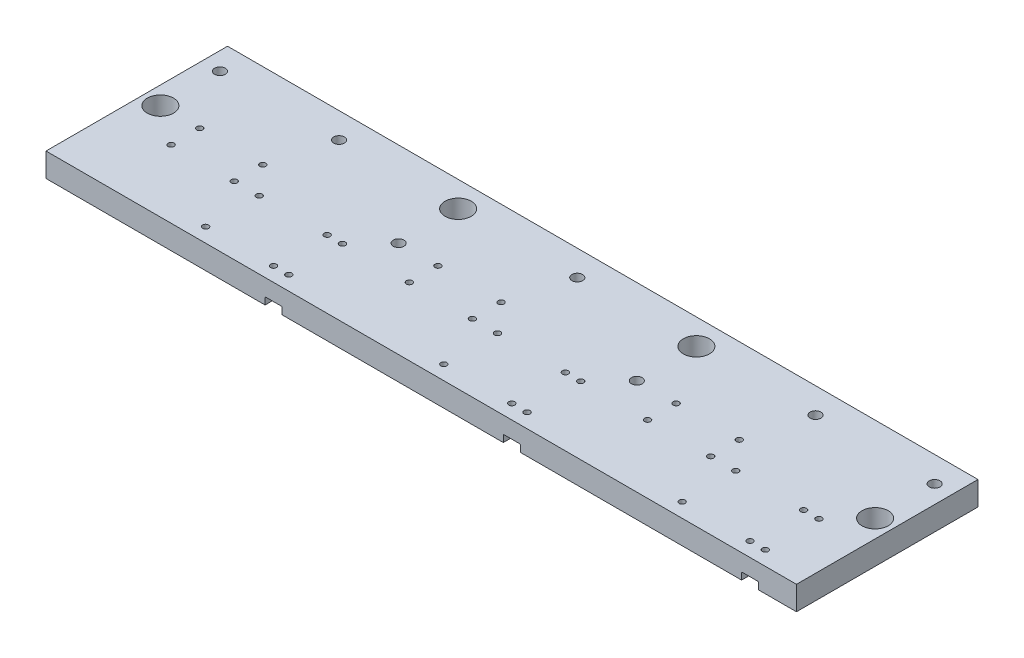
SolidWorks part; units mm, degrees
material "Low Carbon Steel"
ref_plane "Front Plane" through (0, 0, 0) normal (0, 0, 1) x (1, 0, 0)
ref_plane "Top Plane" through (0, 0, 0) normal (0, 1, 0) x (1, 0, 0)
ref_plane "Right Plane" through (0, 0, 0) normal (1, 0, 0) x (0, 0, -1)
sketch "Sketch1" plane through (0, 0, 0) normal (0, 1, 0) x (1, 0, 0)
  line L0 (-315, -76.2) -> (315, 76.2) construction
  line L1 (-315, -76.2) -> (315, -76.2)
  line L2 (-315, -76.2) -> (-315, 76.2)
  line L3 (-315, 76.2) -> (315, 76.2)
  line L4 (315, -76.2) -> (315, 76.2)
  dimension "D1" = 630
  dimension "D2" = 152.4
extrude "Boss-Extrude1" add sketch "Sketch1" along normal mid plane 25.4
sketch "Sketch8" plane through (0, 0, 76.2) normal (0, 0, -1) x (-1, 0, 0)
  line L0 (-83.2, -10) -> (-83.2, -4)
  line L1 (315, 12.7) -> (-315, 12.7)
  line L2 (-315, 12.7) -> (-315, 10)
  line L3 (131.0875, -10) -> (131.0875, -4)
  line L4 (315, 12.7) -> (315, 10)
  line L5 (-83.2, -4) -> (-68.9125, -4)
  line L6 (315, -12.7) -> (-315, -12.7)
  line L7 (315, -12.7) -> (315, -10)
  line L8 (315, -10) -> (131.0875, -10)
  line L9 (-315, -12.7) -> (-315, -10)
  line L10 (315, 12.7) -> (315, -12.7) construction
  line L11 (-315, 12.7) -> (-315, -12.7) construction
  line L12 (-68.9125, -4) -> (-68.9125, -10)
  line L13 (-315, -12.7) -> (315, -12.7) construction
  line L14 (131.0875, -4) -> (116.8, -4)
  line L15 (116.8, -4) -> (116.8, -10)
  line L16 (-283.2, -10) -> (-283.2, -4)
  line L17 (-283.2, -4) -> (-268.9125, -4)
  line L18 (-268.9125, -4) -> (-268.9125, -10)
  line L19 (-283.2, -10) -> (-315, -10)
  line L20 (-83.2, -10) -> (-268.9125, -10)
  line L21 (116.8, -10) -> (-68.9125, -10)
  line L25 (-315, 10) -> (315, 10)
  dimension "D1" = 20
  dimension "D2" = 116.8
  dimension "D3" = 200
  dimension "D4" = 14.2875
  dimension "D5" = 6
  dimension "D6" = 2.7
extrude "Cut-Extrude1" cut sketch "Sketch8" along normal through all
sketch "Sketch23" plane through (0, -10, 0) normal (0, -1, 0) x (1, 0, 0)
  line L0 (-116.8, 6.35) -> (-116.8, -76.2)
  line L1 (-116.8, -76.2) -> (-131.0875, -76.2)
  line L2 (-131.0875, -76.2) -> (-131.0875, 6.35)
  line L3 (-131.0875, -76.2) -> (-131.0875, 76.2) construction
  line L4 (-315, 76.2) -> (-131.0875, 76.2) construction
  line L5 (68.9125, 6.35) -> (68.9125, -76.2)
  line L6 (68.9125, -76.2) -> (68.9125, 76.2) construction
  line L7 (68.9125, -76.2) -> (83.2, -76.2)
  line L8 (83.2, -76.2) -> (83.2, 6.35)
  line L9 (83.2, -76.2) -> (83.2, 76.2) construction
  line L10 (268.9125, 6.35) -> (268.9125, -76.2)
  line L11 (268.9125, -76.2) -> (268.9125, 76.2) construction
  line L12 (268.9125, -76.2) -> (268.9125, 76.2) construction
  line L13 (83.2, -76.2) -> (268.9125, -76.2) construction
  line L14 (268.9125, -76.2) -> (283.2, -76.2)
  line L15 (283.2, -76.2) -> (283.2, 6.35)
  line L16 (283.2, -76.2) -> (283.2, 76.2) construction
  arc A0 (-131.0875, 6.35) -> (-116.8, 6.35) centre (-123.9438, 6.35) ccw
  arc A1 (68.9125, 6.35) -> (83.2, 6.35) centre (76.0563, 6.35) ccw
  arc A2 (268.9125, 6.35) -> (283.2, 6.35) centre (276.0562, 6.35) ccw
  dimension "D1" = 69.85
extrude "Boss-Extrude2" add sketch "Sketch23" against normal up to next
hole_wizard "M8 Clearance Hole1" positions "Sketch3" profile "Sketch2" hole size "M8" standard "Peddi DIN" end condition through all
sketch "Sketch3" plane through (-252.0858, -10, 54.7893) normal (0, -1, 0) x (-1, 0, 0)
  line L9 (-567.0858, -21.4107) -> (-535.2858, -21.4107) construction
  line L10 (-552.0858, 109.5893) -> (-452.0858, 109.5893) construction
  line L11 (-452.0858, 109.5893) -> (-252.0858, 109.5893) construction
  line L12 (-252.0858, 109.5893) -> (-52.0858, 109.5893) construction
  line L13 (-52.0858, 109.5893) -> (47.9142, 109.5893) construction
  line L15 (-252.0858, 109.5893) -> (-252.0858, 54.7893) construction
  line L17 (-352.0858, 59.5893) -> (-352.0858, 109.5893) construction
  line L19 (-152.0858, 59.5893) -> (-152.0858, 109.5893) construction
  point P0 (47.9142, 109.5893)
  point P2 (-52.0858, 109.5893)
  point P4 (-152.0858, 59.5893)
  point P6 (-252.0858, 109.5893)
  point P8 (-352.0858, 59.5893)
  point P10 (-452.0858, 109.5893)
  point P12 (-552.0858, 109.5893)
  dimension "D1" = 100
  dimension "D2" = 50
  dimension "D5" = 131
  dimension "D8" = 200
sketch "Sketch2" plane through (-300, -10, -54.8) normal (1, 0, 0) x (0, 0, -1)
  line L0 (0, 0) -> (0, 20)
  line L1 (0, 20) -> (4.5, 20)
  line L2 (4.5, 20) -> (4.5, 0)
  line L5 (4.5, 0) -> (0, 0)
  line L11 (0, -6.35) -> (0, 107.95) construction
  dimension "Thru Hole Dia." = 9
  dimension "Thru Hole Depth" = 20
hole_wizard "M20 Clearance Hole1" positions "Sketch5" profile "Sketch4" hole size "M20" standard "Peddi DIN" end condition through all
sketch "Sketch5" plane through (-106.6992, -10, 17.1349) normal (0, -1, 0) x (-1, 0, 0)
  line L17 (-406.6992, 71.9349) -> (-406.6992, 21.9349) construction
  line L18 (-406.6992, 21.9349) -> (-206.6992, 21.9349) construction
  line L20 (-206.6992, 21.9349) -> (-206.6992, 71.9349) construction
  line L21 (-206.6992, 71.9349) -> (-106.6992, 71.9349) construction
  line L23 (-106.6992, 71.9349) -> (-6.6992, 71.9349) construction
  line L24 (-6.6992, 71.9349) -> (-6.6992, 21.9349) construction
  line L25 (-6.6992, 21.9349) -> (193.3008, 21.9349) construction
  line L26 (193.3008, 21.9349) -> (193.3008, 71.9349) construction
  point P52 (-406.6992, 21.9349)
  point P61 (-206.6992, 71.9349)
  point P73 (-6.6992, 71.9349)
  point P78 (193.3008, 21.9349)
sketch "Sketch4" plane through (-300, -10, -4.8) normal (1, 0, 0) x (0, 0, -1)
  line L0 (0, 0) -> (0, 20)
  line L1 (0, 20) -> (11, 20)
  line L2 (11, 20) -> (11, 0)
  line L5 (11, 0) -> (0, 0)
  line L11 (0, -6.35) -> (0, 107.95) construction
  dimension "Thru Hole Dia." = 22
  dimension "Thru Hole Depth" = 20
hole_wizard "M6 Tapped Hole2" positions "Sketch7" profile "Sketch6" tap size "M6" standard "Peddi DIN"
sketch "Sketch7" plane through (-22.8298, -10, 14.4386) normal (0, -1, 0) x (-1, 0, 0)
  line L21 (-155.8298, -4.7614) -> (-208.8298, -4.7614) construction
  line L22 (-155.8298, -4.7614) -> (-155.8298, 19.2386) construction
  line L23 (-155.8298, 19.2386) -> (-208.8298, 19.2386) construction
  line L24 (-208.8298, -4.7614) -> (-208.8298, 19.2386) construction
  line L26 (-229.8298, -49.7614) -> (-286.8298, -49.7614) construction
  line L27 (-229.8298, -49.7614) -> (-229.8298, -4.7614) construction
  line L28 (-229.8298, -4.7614) -> (-286.8298, -4.7614) construction
  line L29 (-286.8298, -49.7614) -> (-286.8298, -4.7614) construction
  line L37 (-337.8298, -61.7614) -> (-337.8298, 90.6386) construction
  line L40 (-106.0298, -61.7614) -> (-291.7423, -61.7614) construction
  line L41 (-208.8298, 7.2386) -> (-155.8298, 7.2386) construction
  point P110 (-155.8298, -4.7614)
  point P111 (-208.8298, 19.2386)
  point P140 (-155.8298, 19.2386)
  point P141 (-208.8298, -4.7614)
  point P142 (-229.8298, -49.7614)
  point P143 (-286.8298, -4.7614)
  point P168 (-229.8298, -4.7614)
  point P169 (-286.8298, -49.7614)
  dimension "D2" = 78
  dimension "D3" = 53
  dimension "D4" = 57
  dimension "D5" = 45
  dimension "D6" = 12
  dimension "D7" = 24
  dimension "D12" = 51
sketch "Sketch6" plane through (133, -10, 19.2) normal (1, 0, 0) x (0, 0, -1)
  line L0 (0, 0) -> (0, 29.4922)
  line L1 (0, 29.4922) -> (2.5, 27.99)
  line L2 (2.5, 27.99) -> (2.5, 0)
  line L5 (2.5, 0) -> (0, 0)
  line L10 (0, 29.4922) -> (-2.5, 27.99) construction
  line L11 (0, -6.35) -> (0, 107.95) construction
  dimension "Tap Drill Dia." = 5
  dimension "Tap Drill Depth" = 27.99
  dimension "Drill Angle" = 118
cosmetic thread "Hole Thread1" parameters "D1"=15.01, "D2"=6
cosmetic thread "Hole Thread2" parameters "D1"=15.01, "D2"=6
cosmetic thread "Hole Thread3" parameters "D1"=15.01, "D2"=6
cosmetic thread "Hole Thread4" parameters "D1"=15.01, "D2"=6
cosmetic thread "Hole Thread5" parameters "D1"=15.01, "D2"=6
cosmetic thread "Hole Thread6" parameters "D1"=15.01, "D2"=6
cosmetic thread "Hole Thread7" parameters "D1"=15.01, "D2"=6
cosmetic thread "Hole Thread8" parameters "D1"=15.01, "D2"=6
hole_wizard "M6 Tapped Hole5" positions "Sketch15" profile "Sketch16" tap size "M6" standard "Peddi DIN"
sketch "Sketch15" plane through (0, -10, 0) normal (0, -1, 0) x (-1, 0, 0)
  line L1 (14, 4.8) -> (67, 4.8) construction
  line L2 (14, 4.8) -> (14, -19.2) construction
  line L3 (14, -19.2) -> (67, -19.2) construction
  line L4 (67, 4.8) -> (67, -19.2) construction
  line L6 (-64, -19.2) -> (-7, -19.2) construction
  line L7 (-64, -19.2) -> (-64, -64.2) construction
  line L8 (-64, -64.2) -> (-7, -64.2) construction
  line L9 (-7, -19.2) -> (-7, -64.2) construction
  line L10 (-186, -19.2) -> (-186, 4.8) construction
  line L11 (-264, -64.2) -> (-264, -19.2) construction
  line L12 (-207, -19.2) -> (-264, -19.2) construction
  line L13 (-207, -64.2) -> (-264, -64.2) construction
  line L14 (-133, -19.2) -> (-186, -19.2) construction
  line L15 (-133, 4.8) -> (-186, 4.8) construction
  point P1 (14, 4.8)
  point P2 (67, -19.2)
  point P5 (14, -19.2)
  point P6 (67, 4.8)
  point P41 (-64, -19.2)
  point P42 (-7, -64.2)
  point P45 (-64, -64.2)
  point P46 (-7, -19.2)
  dimension "D1" = 200
  dimension "D2" = 200
sketch "Sketch16" plane through (-14, -10, -4.8) normal (1, 0, 0) x (0, 0, -1)
  line L0 (0, 0) -> (0, 29.4922)
  line L1 (0, 29.4922) -> (2.5, 27.99)
  line L2 (2.5, 27.99) -> (2.5, 0)
  line L5 (2.5, 0) -> (0, 0)
  line L10 (0, 29.4922) -> (-2.5, 27.99) construction
  line L11 (0, -6.35) -> (0, 107.95) construction
  dimension "Tap Drill Dia." = 5
  dimension "Tap Drill Depth" = 27.99
  dimension "Drill Angle" = 118
cosmetic thread "Hole Thread43" parameters "D1"=15.01, "D2"=6
cosmetic thread "Hole Thread44" parameters "D1"=15.01, "D2"=6
cosmetic thread "Hole Thread45" parameters "D1"=15.01, "D2"=6
cosmetic thread "Hole Thread46" parameters "D1"=15.01, "D2"=6
cosmetic thread "Hole Thread47" parameters "D1"=15.01, "D2"=6
cosmetic thread "Hole Thread48" parameters "D1"=15.01, "D2"=6
cosmetic thread "Hole Thread49" parameters "D1"=15.01, "D2"=6
cosmetic thread "Hole Thread50" parameters "D1"=15.01, "D2"=6
hole_wizard "M6 Tapped Hole6" positions "Sketch17" profile "Sketch18" tap size "M6" standard "Peddi DIN"
sketch "Sketch17" plane through (0, -10, 0) normal (0, -1, 0) x (-1, 0, 0)
  line L1 (136, -19.2) -> (193, -19.2) construction
  line L2 (136, -19.2) -> (136, -64.2) construction
  line L3 (136, -64.2) -> (193, -64.2) construction
  line L4 (193, -19.2) -> (193, -64.2) construction
  line L6 (214, 4.8) -> (267, 4.8) construction
  line L7 (214, 4.8) -> (214, -19.2) construction
  line L8 (214, -19.2) -> (267, -19.2) construction
  line L9 (267, 4.8) -> (267, -19.2) construction
  line L10 (-207, -19.2) -> (-264, -19.2) construction
  line L11 (-133, 4.8) -> (-186, 4.8) construction
  line L12 (-133, -19.2) -> (-186, -19.2) construction
  line L13 (-207, -64.2) -> (-264, -64.2) construction
  line L14 (-264, -64.2) -> (-264, -19.2) construction
  line L15 (-186, -19.2) -> (-186, 4.8) construction
  point P1 (136, -19.2)
  point P2 (193, -64.2)
  point P5 (136, -64.2)
  point P6 (193, -19.2)
  point P87 (214, 4.8)
  point P88 (267, -19.2)
  point P91 (214, -19.2)
  point P92 (267, 4.8)
  dimension "D1" = 400
  dimension "D2" = 400
sketch "Sketch18" plane through (-136, -10, 19.2) normal (1, 0, 0) x (0, 0, -1)
  line L0 (0, 0) -> (0, 29.4922)
  line L1 (0, 29.4922) -> (2.5, 27.99)
  line L2 (2.5, 27.99) -> (2.5, 0)
  line L5 (2.5, 0) -> (0, 0)
  line L10 (0, 29.4922) -> (-2.5, 27.99) construction
  line L11 (0, -6.35) -> (0, 107.95) construction
  dimension "Tap Drill Dia." = 5
  dimension "Tap Drill Depth" = 27.99
  dimension "Drill Angle" = 118
cosmetic thread "Hole Thread51" parameters "D1"=15.01, "D2"=6
cosmetic thread "Hole Thread52" parameters "D1"=15.01, "D2"=6
cosmetic thread "Hole Thread53" parameters "D1"=15.01, "D2"=6
cosmetic thread "Hole Thread54" parameters "D1"=15.01, "D2"=6
cosmetic thread "Hole Thread55" parameters "D1"=15.01, "D2"=6
cosmetic thread "Hole Thread56" parameters "D1"=15.01, "D2"=6
cosmetic thread "Hole Thread57" parameters "D1"=15.01, "D2"=6
cosmetic thread "Hole Thread58" parameters "D1"=15.01, "D2"=6
hole_wizard "M6 Tapped Hole3" positions "Sketch11" profile "Sketch9" tap size "M6" standard "Peddi DIN"
sketch "Sketch11" plane through (0, -4, 0) normal (0, -1, 0) x (-1, 0, 0)
  line L4 (-264, -19.2) -> (-276.85, -19.2) construction
  line L5 (-276.85, -19.2) -> (-276.85, -64.2) construction
  line L6 (-276.85, -64.2) -> (-264, -64.2) construction
  line L13 (-283.2, -6.35) -> (-283.2, -76.2) construction
  point P20 (-276.85, -19.2)
  point P22 (-276.85, -64.2)
  dimension "D1" = 6.35
sketch "Sketch9" plane through (276.85, -4, 19.2) normal (1, 0, 0) x (0, 0, -1)
  line L0 (0, 0) -> (0, 29.4922)
  line L1 (0, 29.4922) -> (2.5, 27.99)
  line L2 (2.5, 27.99) -> (2.5, 0)
  line L5 (2.5, 0) -> (0, 0)
  line L10 (0, 29.4922) -> (-2.5, 27.99) construction
  line L11 (0, -6.35) -> (0, 107.95) construction
  dimension "Tap Drill Dia." = 5
  dimension "Tap Drill Depth" = 27.99
  dimension "Drill Angle" = 118
cosmetic thread "Hole Thread37" parameters "D1"=14, "D2"=6
cosmetic thread "Hole Thread38" parameters "D1"=14, "D2"=6
hole_wizard "M6 Tapped Hole7" positions "Sketch19" profile "Sketch20" tap size "M6" standard "Peddi DIN"
sketch "Sketch19" plane through (0, -4, 0) normal (0, -1, 0) x (-1, 0, 0)
  line L0 (-64, -19.2) -> (-76.85, -19.2) construction
  line L1 (-76.85, -19.2) -> (-76.85, -64.2) construction
  line L2 (-76.85, -64.2) -> (-64, -64.2) construction
  line L4 (-264, -19.2) -> (-276.85, -19.2) construction
  point P0 (-76.85, -19.2)
  point P2 (-76.85, -64.2)
sketch "Sketch20" plane through (76.85, -4, 19.2) normal (1, 0, 0) x (0, 0, -1)
  line L0 (0, 0) -> (0, 29.4922)
  line L1 (0, 29.4922) -> (2.5, 27.99)
  line L2 (2.5, 27.99) -> (2.5, 0)
  line L5 (2.5, 0) -> (0, 0)
  line L10 (0, 29.4922) -> (-2.5, 27.99) construction
  line L11 (0, -6.35) -> (0, 107.95) construction
  dimension "Tap Drill Dia." = 5
  dimension "Tap Drill Depth" = 27.99
  dimension "Drill Angle" = 118
cosmetic thread "Hole Thread59" parameters "D1"=14, "D2"=6
cosmetic thread "Hole Thread60" parameters "D1"=14, "D2"=6
hole_wizard "M6 Tapped Hole8" positions "Sketch21" profile "Sketch22" tap size "M6" standard "Peddi DIN"
sketch "Sketch21" plane through (0, -4, 0) normal (0, -1, 0) x (-1, 0, 0)
  line L0 (136, -19.2) -> (123.15, -19.2) construction
  line L1 (123.15, -19.2) -> (123.15, -64.2) construction
  line L2 (123.15, -64.2) -> (136, -64.2) construction
  line L4 (-264, -19.2) -> (-276.85, -19.2) construction
  point P0 (123.15, -19.2)
  point P2 (123.15, -64.2)
sketch "Sketch22" plane through (-123.15, -4, 19.2) normal (1, 0, 0) x (0, 0, -1)
  line L0 (0, 0) -> (0, 29.4922)
  line L1 (0, 29.4922) -> (2.5, 27.99)
  line L2 (2.5, 27.99) -> (2.5, 0)
  line L5 (2.5, 0) -> (0, 0)
  line L10 (0, 29.4922) -> (-2.5, 27.99) construction
  line L11 (0, -6.35) -> (0, 107.95) construction
  dimension "Tap Drill Dia." = 5
  dimension "Tap Drill Depth" = 27.99
  dimension "Drill Angle" = 118
cosmetic thread "Hole Thread61" parameters "D1"=14, "D2"=6
cosmetic thread "Hole Thread62" parameters "D1"=14, "D2"=6
ref_plane "Plane1" through (-267, 0, 0) normal (1, 0, 0) x (0, 0, -1)
ref_plane "Plane2" through (0, 0, 7.2) normal (0, 0, 1) x (1, 0, 0)
fillet "Fillet1" radius 0.7937 9 edges at (268.9125, -4, 41.275) (283.2, -4, 41.275) (83.2, -4, 41.275) (68.9125, -4, 41.275) (-131.0875, -4, 41.275) (-116.8, -4, 41.275) (276.0562, -4, -0.7937) (76.0563, -4, -0.7937) (-123.9438, -4, -0.7937)
sketch "datum a" plane through (0, -10, 0) normal (0, -1, 0) x (1, 0, 0)
  line L0 (-315, 76.2) -> (-131.0875, 76.2) construction
  line L1 (-200.9375, 76.2) -> (-131.0875, 76.2)
  line L2 (-200.9375, 76.2) -> (-200.9375, -3.175)
  line L3 (-200.9375, -3.175) -> (-131.0875, -3.175)
  line L4 (-131.0875, 76.2) -> (-131.0875, -3.175)
  line L5 (-131.0875, 6.35) -> (-131.0875, 76.2) construction
  line L6 (-116.8, 76.2) -> (68.9125, 76.2) construction
  line L7 (-0.9375, 76.2) -> (68.9125, 76.2)
  line L8 (-0.9375, 76.2) -> (-0.9375, -3.175)
  line L9 (-0.9375, -3.175) -> (68.9125, -3.175)
  line L10 (68.9125, 76.2) -> (68.9125, -3.175)
  line L11 (68.9125, 6.35) -> (68.9125, 76.2) construction
  line L12 (83.2, 76.2) -> (268.9125, 76.2) construction
  line L13 (199.0625, 76.2) -> (268.9125, 76.2)
  line L14 (199.0625, 76.2) -> (199.0625, -3.175)
  line L15 (199.0625, -3.175) -> (268.9125, -3.175)
  line L16 (268.9125, 76.2) -> (268.9125, -3.175)
  line L17 (268.9125, 6.35) -> (268.9125, 76.2) construction
  dimension "D1" = 69.85
  dimension "D2" = 79.375
other "Freeze***"
